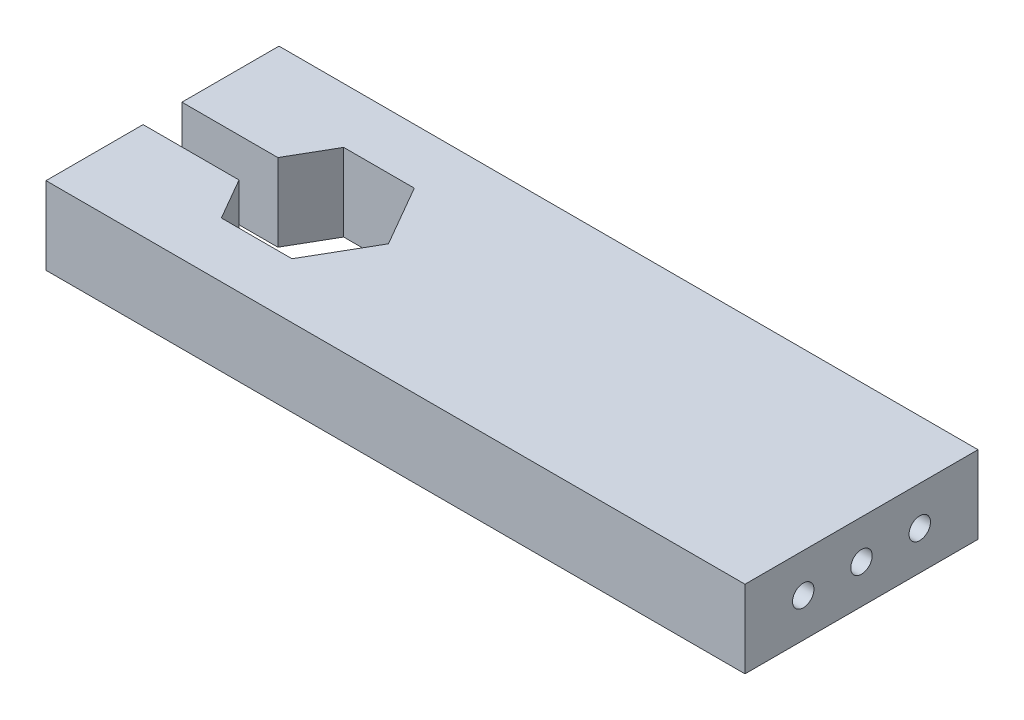
SolidWorks part; units mm, degrees
ref_plane "Front" through (0, 0, 0) normal (0, 0, 1) x (1, 0, 0)
ref_plane "Top" through (0, 0, 0) normal (0, 1, 0) x (1, 0, 0)
ref_plane "Right" through (0, 0, 0) normal (1, 0, 0) x (0, 0, -1)
sketch "Sketch1" plane through (0, 0, 0) normal (0, 1, 0) x (1, 0, 0)
  line L1 (0, -19.05) -> (-114.3, -19.05)
  line L2 (0, -19.05) -> (0, 19.05)
  line L3 (0, 19.05) -> (-114.3, 19.05)
  line L4 (-114.3, -19.05) -> (-114.3, 19.05)
  line L5 (0, -19.05) -> (-114.3, 19.05) construction
  line L6 (0, 19.05) -> (-114.3, -19.05) construction
  dimension "D1" = 38.1
  dimension "D2" = 114.3
extrude "Boss-Extrude1" add sketch "Sketch1" along normal mid plane 12.7
hole_wizard "#6-32 Threaded Hole" positions "Sketch4" profile "Sketch3" hole size "#97" standard "ANSI Inch"
sketch "Sketch4" plane through (0, 0, 0) normal (1, 0, 0) x (0, 0, -1)
  point P0 (0, 0)
  point P3 (9.525, 0)
  point P5 (-9.525, 0)
  dimension "D1" = 9.525
  dimension "D2" = 9.525
sketch "Sketch3" plane through (0, 0, 0) normal (0, 1, 0) x (0, 0, -1)
  line L0 (0, 0) -> (0, 51.8531)
  line L1 (0, 51.8531) -> (1.7526, 50.8)
  line L2 (1.7526, 50.8) -> (1.7526, 0)
  line L5 (1.7526, 0) -> (0, 0)
  line L10 (0, 51.8531) -> (-1.7526, 50.8) construction
  line L11 (0, -6.35) -> (0, 107.95) construction
  dimension "Hole Dia." = 3.5052
  dimension "Hole Depth" = 50.8
  dimension "Drill Angle" = 118
sketch "Sketch5" plane through (0, 6.35, 0) normal (0, 1, 0) x (1, 0, 0)
  line L0 (0, -19.05) -> (0, 19.05) construction
  line L1 (-83.1265, -10) -> (-77.353, 0)
  line L2 (-77.353, 0) -> (-83.1265, 10)
  line L3 (-83.1265, 10) -> (-94.6735, 10)
  line L4 (-94.6735, 10) -> (-100.447, 0)
  line L5 (-100.447, 0) -> (-94.6735, -10)
  line L6 (-94.6735, -10) -> (-83.1265, -10)
  line L7 (0, 19.05) -> (-114.3, 19.05) construction
  circle A0 centre (-88.9, 0) radius 10 construction
  point P1 (0, 0)
  dimension "D1" = 20
  dimension "D2" = 88.9
extrude "Cut-Extrude1" cut sketch "Sketch5" against normal up to surface (12.7 mm away) up to face at (-57.15, -6.35, 0)
sketch "Sketch8" plane through (0, 6.35, 0) normal (0, 1, 0) x (1, 0, 0)
  line L0 (-114.3, 19.05) -> (-114.3, -19.05) construction
  line L1 (-94.6735, -3.175) -> (-114.3, -3.175)
  line L2 (-94.6735, -3.175) -> (-94.6735, 3.175)
  line L3 (-94.6735, 3.175) -> (-114.3, 3.175)
  line L4 (-114.3, -3.175) -> (-114.3, 3.175)
  line L5 (0, 0) -> (-114.3, 0) construction
  line L6 (0, -19.05) -> (0, 19.05) construction
  point P14 (-94.6735, 0)
  dimension "D1" = 6.35
extrude "Cut-Extrude2" cut sketch "Sketch8" against normal through all
